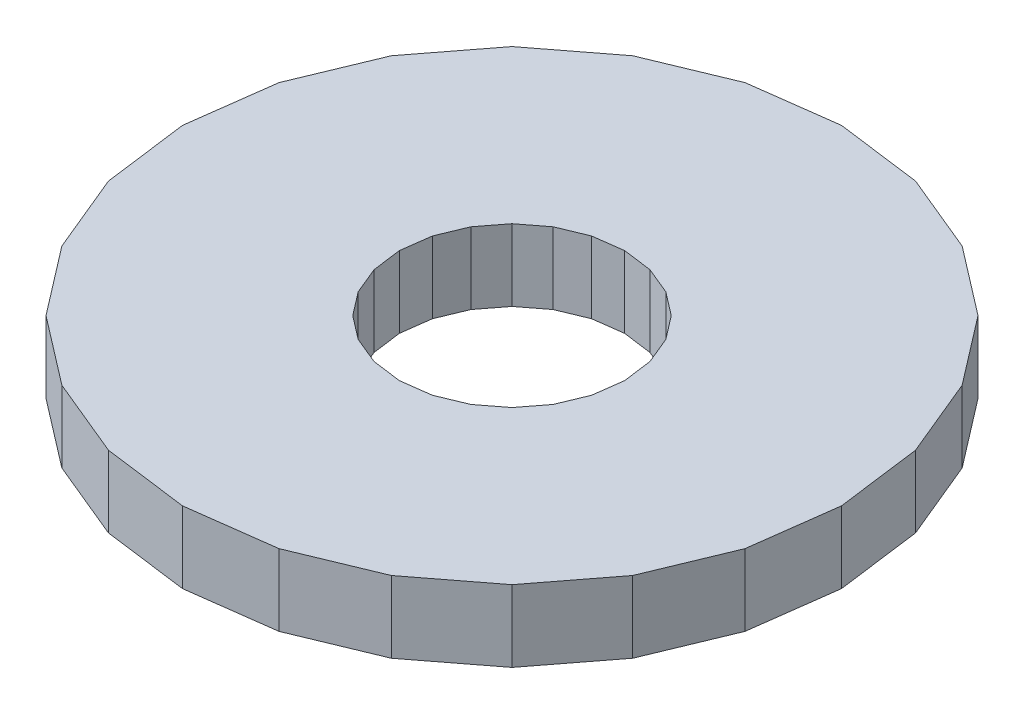
SolidWorks part; units mm, degrees
ref_plane "Front Plane" through (0, 0, 0) normal (0, 0, 1) x (1, 0, 0)
ref_plane "Top Plane" through (0, 0, 0) normal (0, 1, 0) x (1, 0, 0)
ref_plane "Right Plane" through (0, 0, 0) normal (1, 0, 0) x (0, 0, -1)
sketch "Sketch1" plane through (0, 0, 0) normal (0, 1, 0) x (1, 0, 0)
  line L0 (0, 0) -> (-29.9255, 0) construction
  line L1 (87.5686, 0) -> (84.5848, 22.6644)
  line L2 (84.5848, 22.6644) -> (75.8367, 43.7843)
  line L3 (75.8367, 43.7843) -> (61.9204, 61.9204)
  line L4 (61.9204, 61.9204) -> (43.7843, 75.8367)
  line L5 (43.7843, 75.8367) -> (22.6644, 84.5848)
  line L6 (22.6644, 84.5848) -> (0, 87.5686)
  line L7 (0, 87.5686) -> (-22.6644, 84.5848)
  line L8 (-22.6644, 84.5848) -> (-43.7843, 75.8367)
  line L9 (-43.7843, 75.8367) -> (-61.9204, 61.9204)
  line L10 (-61.9204, 61.9204) -> (-75.8367, 43.7843)
  line L11 (-75.8367, 43.7843) -> (-84.5848, 22.6644)
  line L12 (-84.5848, 22.6644) -> (-87.5686, 0)
  line L13 (-87.5686, 0) -> (-84.5848, -22.6644)
  line L14 (-84.5848, -22.6644) -> (-75.8367, -43.7843)
  line L15 (-75.8367, -43.7843) -> (-61.9204, -61.9204)
  line L16 (-61.9204, -61.9204) -> (-43.7843, -75.8367)
  line L17 (-43.7843, -75.8367) -> (-22.6644, -84.5848)
  line L18 (-22.6644, -84.5848) -> (0, -87.5686)
  line L19 (0, -87.5686) -> (22.6644, -84.5848)
  line L20 (22.6644, -84.5848) -> (43.7843, -75.8367)
  line L21 (43.7843, -75.8367) -> (61.9204, -61.9204)
  line L22 (61.9204, -61.9204) -> (75.8367, -43.7843)
  line L23 (75.8367, -43.7843) -> (84.5848, -22.6644)
  line L24 (84.5848, -22.6644) -> (87.5686, 0)
  line L25 (29.9255, 0) -> (28.9058, 7.7453)
  line L26 (28.9058, 7.7453) -> (25.9162, 14.9627)
  line L27 (25.9162, 14.9627) -> (21.1605, 21.1605)
  line L28 (21.1605, 21.1605) -> (14.9627, 25.9162)
  line L29 (14.9627, 25.9162) -> (7.7453, 28.9058)
  line L30 (7.7453, 28.9058) -> (0, 29.9255)
  line L31 (0, 29.9255) -> (-7.7453, 28.9058)
  line L32 (-7.7453, 28.9058) -> (-14.9627, 25.9162)
  line L33 (-14.9627, 25.9162) -> (-21.1605, 21.1605)
  line L34 (-21.1605, 21.1605) -> (-25.9162, 14.9627)
  line L35 (-25.9162, 14.9627) -> (-28.9058, 7.7453)
  line L36 (-28.9058, 7.7453) -> (-29.9255, 0)
  line L37 (-29.9255, 0) -> (-28.9058, -7.7453)
  line L38 (-28.9058, -7.7453) -> (-25.9162, -14.9627)
  line L39 (-25.9162, -14.9627) -> (-21.1605, -21.1605)
  line L40 (-21.1605, -21.1605) -> (-14.9627, -25.9162)
  line L41 (-14.9627, -25.9162) -> (-7.7453, -28.9058)
  line L42 (-7.7453, -28.9058) -> (0, -29.9255)
  line L43 (0, -29.9255) -> (7.7453, -28.9058)
  line L44 (7.7453, -28.9058) -> (14.9627, -25.9162)
  line L45 (14.9627, -25.9162) -> (21.1605, -21.1605)
  line L46 (21.1605, -21.1605) -> (25.9162, -14.9627)
  line L47 (25.9162, -14.9627) -> (28.9058, -7.7453)
  line L48 (28.9058, -7.7453) -> (29.9255, 0)
  line L49 (-29.9255, 0) -> (-87.5686, 0) construction
  circle A0 centre (0, 0) radius 86.8195 construction
  circle A1 centre (0, 0) radius 29.6695 construction
  dimension "D1" = 57.15
  dimension "D2" = 22.86
extrude "Boss-Extrude1" add sketch "Sketch1" along normal blind 19.05
